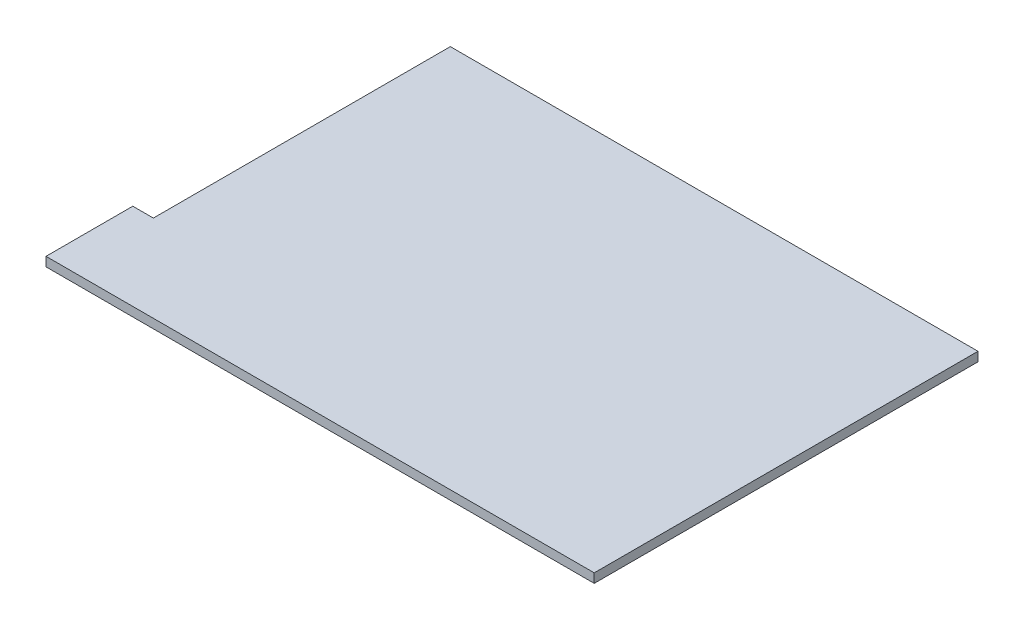
SolidWorks part; units mm, degrees
ref_plane "Front Plane" through (0, 0, 0) normal (0, 0, 1) x (1, 0, 0)
ref_plane "Top Plane" through (0, 0, 0) normal (0, 1, 0) x (1, 0, 0)
ref_plane "Right Plane" through (0, 0, 0) normal (1, 0, 0) x (0, 0, -1)
sketch "Sketch1" plane through (0, 0, 0) normal (0, 1, 0) x (1, 0, 0)
  line L1 (0, 533.4) -> (762, 533.4)
  line L2 (0, 533.4) -> (0, 0)
  line L3 (0, 0) -> (762, 0)
  line L4 (762, 533.4) -> (762, 0)
  line L5 (0, 533.4) -> (762, 0) construction
  line L6 (0, 0) -> (762, 533.4) construction
  point P0 (-2.6304, 18.4824)
  dimension "D1" = 533.4
  dimension "D2" = 762
extrude "Boss-Extrude1" add sketch "Sketch1" along normal blind 12.7
sketch "Sketch2" plane through (0, 0, 0) normal (0, -1, 0) x (1, 0, 0)
  line L5 (0, -533.4) -> (28.575, -533.4)
  line L6 (0, -533.4) -> (0, -120.65)
  line L7 (0, -120.65) -> (28.575, -120.65)
  line L8 (28.575, -533.4) -> (28.575, -120.65)
  dimension "D1" = 28.575
  dimension "D2" = 412.75
extrude "Cut-Extrude1" cut sketch "Sketch2" against normal through all
